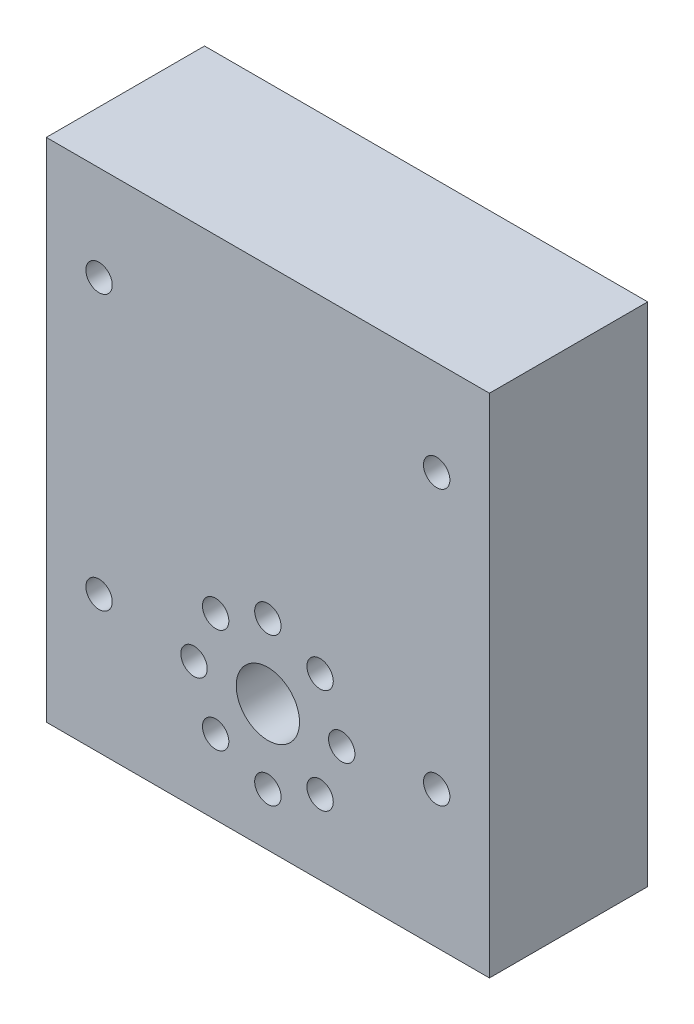
SolidWorks part; units mm, degrees
material "自訂玻璃纖維"
ref_plane "前基準面" through (0, 0, 0) normal (0, 0, 1) x (1, 0, 0)
ref_plane "上基準面" through (0, 0, 0) normal (0, 1, 0) x (1, 0, 0)
ref_plane "右基準面" through (0, 0, 0) normal (1, 0, 0) x (0, 0, -1)
sketch "草圖1" plane through (0, 0, 0) normal (0, 0, 1) x (1, 0, 0)
  line L1 (-41.8137, 14.9796) -> (0.1863, 14.9796)
  line L2 (-41.8137, 14.9796) -> (-41.8137, -33.0204)
  line L3 (-41.8137, -33.0204) -> (0.1863, -33.0204)
  line L4 (0.1863, 14.9796) -> (0.1863, -33.0204)
  circle A0 centre (-36.8137, 5.9796) radius 1.25
  circle A1 centre (-36.8137, -20.0204) radius 1.25
  circle A2 centre (-4.8137, -20.0204) radius 1.25
  circle A3 centre (-4.8137, 5.9796) radius 1.25
  dimension "D3" = 2.5
  dimension "D4" = 26
  dimension "D1" = 5
  dimension "D2" = 26
  dimension "D8" = 5
  dimension "D6" = 9
  dimension "D10" = 9
  dimension "D5" = 48
  dimension "D7" = 5
  dimension "D9" = 5
extrude "填料-伸長1" add sketch "草圖1" along normal blind 15
sketch "草圖2" plane through (0, 0, 15) normal (0, 0, 1) x (1, 0, 0)
  line L1 (-41.8137, -33.0204) -> (0.1863, -33.0204) construction
  circle A0 centre (-20.8137, -21.0204) radius 3
  circle A1 centre (-20.8137, -14.0204) radius 1.25
  circle A2 centre (-25.7635, -16.0707) radius 1.25
  circle A3 centre (-27.8137, -21.0204) radius 1.25
  circle A4 centre (-25.7635, -25.9701) radius 1.25
  circle A5 centre (-20.8137, -28.0204) radius 1.25
  circle A6 centre (-15.864, -25.9701) radius 1.25
  circle A7 centre (-13.8137, -21.0204) radius 1.25
  circle A8 centre (-15.864, -16.0707) radius 1.25
  point P7 (-20.8137, -33.0204)
  point P23 (-20.8137, -13.0204)
  point P25 (-25.6422, -19.0204)
  point P26 (-20.8137, -21.0204)
  dimension "D1" = 6
  dimension "D2" = 12
  dimension "D3" = 8
  dimension "D4" = 7
extrude "除料-伸長1" cut sketch "草圖2" against normal blind 20
